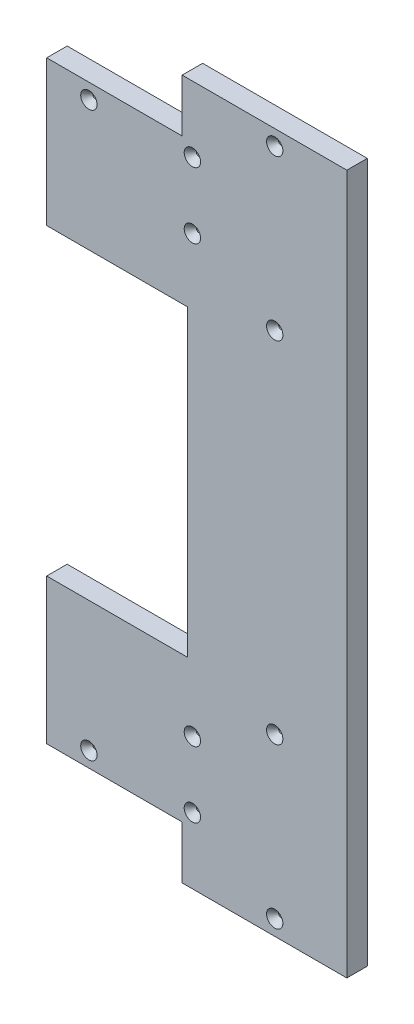
SolidWorks part; units mm, degrees
material "Beech"
ref_plane "Front Plane" through (0, 0, 0) normal (0, 0, 1) x (1, 0, 0)
ref_plane "Top Plane" through (0, 0, 0) normal (0, 1, 0) x (1, 0, 0)
ref_plane "Right Plane" through (0, 0, 0) normal (1, 0, 0) x (0, 0, -1)
sketch "Sketch1" plane through (0, 0, 0) normal (0, 0, 1) x (1, 0, 0)
  line L1 (-81.8518, 217.3) -> (161.737, 217.3)
  line L2 (-81.8518, 217.3) -> (-81.8518, -217.3)
  line L3 (-81.8518, -217.3) -> (161.737, -217.3)
  line L4 (161.737, 217.3) -> (161.737, -217.3)
  line L5 (72.1361, 217.3) -> (161.737, 217.3) construction
extrude "Boss-Extrude1" add sketch "Sketch1" along normal blind 12.7
sketch "Sketch2" plane through (0, 0, 0) normal (0, 0, -1) x (-1, 0, 0)
  line L1 (-59.4361, 184.525) -> (81.8518, 184.525)
  line L2 (-59.4361, 184.525) -> (-59.4361, 217.3)
  line L3 (-59.4361, 217.3) -> (81.8518, 217.3)
  line L4 (81.8518, 184.525) -> (81.8518, 217.3)
  line L5 (-59.4361, -184.525) -> (81.8518, -184.525)
  line L6 (-59.4361, -184.525) -> (-59.4361, -217.3)
  line L7 (-59.4361, -217.3) -> (81.8518, -217.3)
  line L8 (81.8518, -184.525) -> (81.8518, -217.3)
extrude "Cut-Extrude1" cut sketch "Sketch2" against normal up to next
sketch "Sketch3" plane through (0, 0, 12.7) normal (0, 0, 1) x (1, 0, 0)
  line L0 (-81.8518, 184.525) -> (-81.8518, -184.525) construction
  line L1 (59.4361, 91.075) -> (-81.8518, 91.075) construction
  line L2 (59.4361, 91.075) -> (59.4361, -91.075) construction
  line L3 (59.4361, -91.075) -> (-81.8518, -91.075) construction
  line L4 (-81.8518, 91.075) -> (-81.8518, -91.075) construction
  line L5 (-81.8518, 91.075) -> (59.4361, 91.075) construction
  line L6 (-81.8518, -91.075) -> (59.4361, -91.075) construction
  line L7 (59.4361, 165.475) -> (59.4361, -165.475) construction
  line L8 (62.6111, 94.25) -> (-56.4518, 94.25)
  line L9 (-85.0268, 94.25) -> (-85.0268, -94.25)
  line L10 (62.6111, -94.25) -> (-56.4518, -94.25)
  line L11 (62.6111, 94.25) -> (62.6111, -94.25)
  line L12 (-81.8518, 94.25) -> (-85.0268, 94.25)
  line L13 (-81.8518, 184.525) -> (-56.4518, 184.525)
  line L14 (-81.8518, 184.525) -> (-81.8518, 94.25)
  line L16 (-56.4518, 184.525) -> (-56.4518, 94.25)
  line L17 (62.6111, 94.25) -> (-85.0268, 94.25) construction
  line L18 (-81.8518, -94.25) -> (-85.0268, -94.25)
  line L19 (-81.8518, -184.525) -> (-56.4518, -184.525)
  line L20 (-81.8518, -184.525) -> (-81.8518, -94.25)
  line L22 (-56.4518, -184.525) -> (-56.4518, -94.25)
  line L23 (62.6111, -94.25) -> (-85.0268, -94.25) construction
  dimension "D2" = 25.4
  dimension "D1" = 3.175
extrude "Cut-Extrude2" cut sketch "Sketch3" against normal up to next
hole_wizard "Hole1" positions "Sketch4" profile "Sketch5" legacy
sketch "Sketch4" plane through (449.8285, 0, 12.7) normal (0, 0, 1) x (0, 1, 0)
  line L0 (207.775, 377.6924) -> (207.775, 288.0915) construction
  line L4 (108.65, 377.6924) -> (108.65, 288.0915) construction
  line L8 (175, 506.2803) -> (175, 390.3924) construction
  line L12 (94.25, 390.3924) -> (94.25, 377.6924) construction
  line L17 (94.25, 384.0424) -> (217.3, 384.0424) construction
  line L19 (94.25, 384.0424) -> (135.2667, 384.0424)
  line L20 (135.2667, 384.0424) -> (176.2833, 384.0424)
  line L21 (176.2833, 384.0424) -> (217.3, 384.0424)
  line L22 (0, 288.0915) -> (0, 390.3924) construction
  point P39 (108.65, 332.8919)
  point P41 (207.775, 332.8919)
  point P43 (175, 448.3363)
  point P47 (135.2667, 384.0424)
  point P49 (176.2833, 384.0424)
  point P65 (-175, 448.3363)
  point P66 (-135.2667, 384.0424)
  point P67 (-176.2833, 384.0424)
  point P68 (-207.775, 332.8919)
  point P69 (-108.65, 332.8919)
sketch "Sketch5" plane through (116.9365, -108.65, 12.7) normal (1, 0, 0) x (0, -1, 0)
  line L0 (0, 0) -> (0, 39.0539)
  line L1 (0, 39.0539) -> (1.5875, 38.1)
  line L2 (1.5875, 38.1) -> (1.5875, 4.0177)
  line L3 (1.5875, 4.0177) -> (5.08, 0)
  line L4 (5.08, 0) -> (0, 0)
  line L5 (0, -14.3089) -> (0, 102.4216) construction
  line L6 (0, 39.0539) -> (-1.5875, 38.1) construction
  line L7 (-1.5875, 4.0177) -> (-5.08, 0) construction
  dimension "Diameter" = 3.175
  dimension "Depth" = 38.1
  dimension "C-Sink Diameter" = 10.16
  dimension "C-Sink Angle" = 82
  dimension "Drill Angle" = 118
sketch "Sketch6" plane through (0, 0, 12.7) normal (0, 0, 1) x (1, 0, 0)
  line L0 (62.6111, 94.25) -> (-56.4518, 94.25) construction
  line L1 (-56.4518, 184.525) -> (-24.7018, 184.525)
  line L2 (-56.4518, 184.525) -> (-56.4518, 94.25)
  line L3 (-56.4518, 94.25) -> (-24.7018, 94.25)
  line L4 (-24.7018, 184.525) -> (-24.7018, 94.25)
  line L5 (-56.4518, -94.25) -> (62.6111, -94.25) construction
  line L6 (-56.4518, -184.525) -> (-24.7018, -184.525)
  line L7 (-56.4518, -184.525) -> (-56.4518, -94.25)
  line L8 (-56.4518, -94.25) -> (-24.7018, -94.25)
  line L9 (-24.7018, -184.525) -> (-24.7018, -94.25)
  dimension "D1" = 31.75
extrude "Cut-Extrude3" cut sketch "Sketch6" against normal up to next
